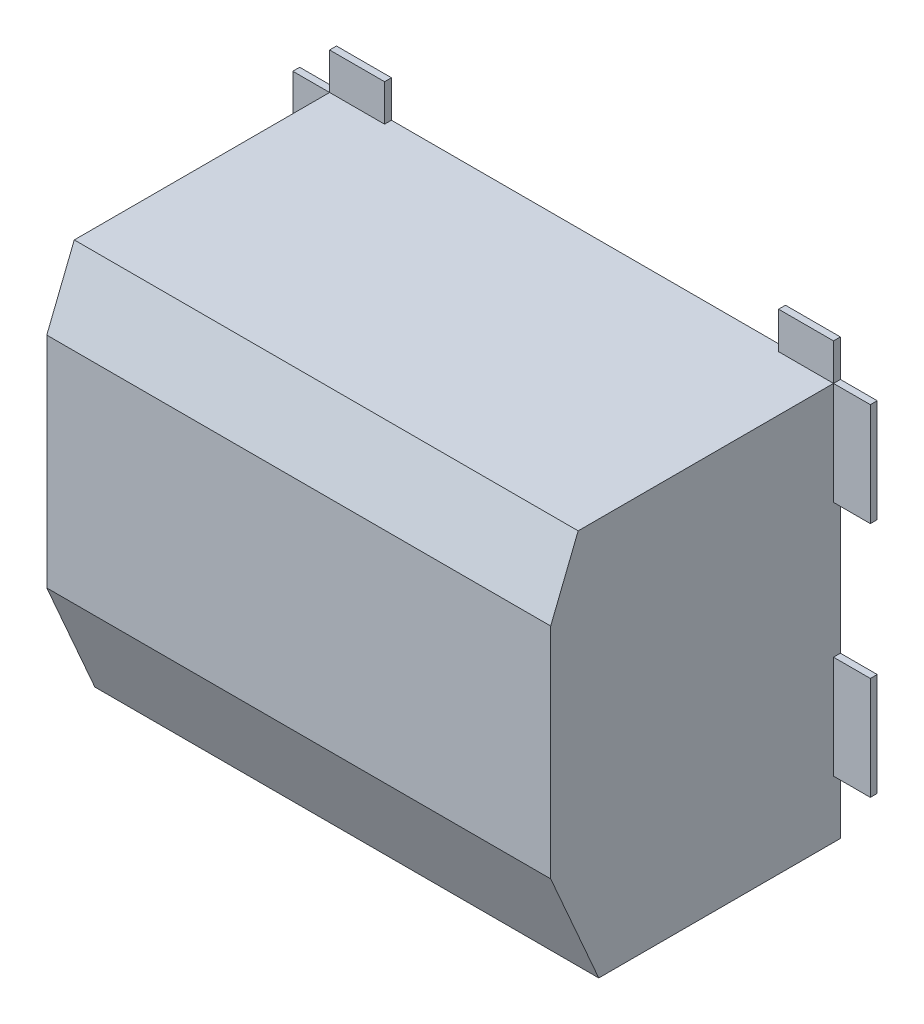
SolidWorks part; units mm, degrees
material "6061-T6 (SS)"
ref_plane "X-Y Datum" through (0, 0, 0) normal (0, 0, 1) x (1, 0, 0)
ref_plane "X-Z Datum" through (0, 0, 0) normal (0, 1, 0) x (1, 0, 0)
ref_plane "Y-Z Datum" through (0, 0, 0) normal (1, 0, 0) x (0, 0, -1)
sketch "Sketch1" plane through (0, 0, 0) normal (0, 0, 1) x (1, 0, 0)
  line L0 (-276.2265, 0) -> (276.2265, 0) construction
  line L1 (-276.2265, 154.041) -> (276.2265, 154.041)
  line L2 (-276.2265, 154.041) -> (-276.2265, -154.041)
  line L3 (-276.2265, -154.041) -> (276.2265, -154.041)
  line L4 (276.2265, 154.041) -> (276.2265, -154.041)
  line L5 (-276.2265, 154.041) -> (276.2265, -154.041) construction
  line L6 (-276.2265, -154.041) -> (276.2265, 154.041) construction
  line L7 (-275.2105, 153.025) -> (-189.6105, 153.025) construction
  line L8 (-275.2105, 153.025) -> (-275.2105, -153.025) construction
  line L9 (-275.2105, -153.025) -> (-189.6105, -153.025) construction
  line L10 (-189.6105, 153.025) -> (-189.6105, -153.025) construction
  line L11 (-275.2105, 153.025) -> (-189.6105, -153.025) construction
  line L12 (-275.2105, -153.025) -> (-189.6105, 153.025) construction
  line L13 (-188.5945, -154.041) -> (-188.5945, 154.041)
  line L14 (-279.4015, 157.216) -> (279.4015, 157.216)
  line L15 (279.4015, 157.216) -> (279.4015, -157.216)
  line L16 (-279.4015, -157.216) -> (279.4015, -157.216)
  line L17 (-279.4015, 157.216) -> (-279.4015, -157.216)
  line L18 (-185.4195, -154.041) -> (-185.4195, 154.041)
  line L19 (-188.5945, 0) -> (-185.4195, 0) construction
  line L20 (-182.2465, 153.025) -> (-182.2465, -153.025) construction
  line L21 (-182.2465, 153.025) -> (-96.6465, 153.025) construction
  line L22 (-96.6465, 153.025) -> (-96.6465, -153.025) construction
  line L23 (-182.2465, -153.025) -> (-96.6465, -153.025) construction
  line L24 (-95.6305, -154.041) -> (-95.6305, 154.041)
  line L25 (-92.4555, -154.041) -> (-92.4555, 154.041)
  line L26 (-89.2825, 153.025) -> (-89.2825, -153.025) construction
  line L27 (-89.2825, 153.025) -> (-3.6825, 153.025) construction
  line L28 (-3.6825, 153.025) -> (-3.6825, -153.025) construction
  line L29 (-89.2825, -153.025) -> (-3.6825, -153.025) construction
  line L30 (-2.6665, -154.041) -> (-2.6665, 154.041)
  line L31 (0.5085, -154.041) -> (0.5085, 154.041)
  line L32 (3.6815, 153.025) -> (3.6815, -153.025) construction
  line L33 (3.6815, 153.025) -> (89.2815, 153.025) construction
  line L34 (89.2815, 153.025) -> (89.2815, -153.025) construction
  line L35 (3.6815, -153.025) -> (89.2815, -153.025) construction
  line L36 (90.2975, -154.041) -> (90.2975, 154.041)
  line L37 (93.4725, -154.041) -> (93.4725, 154.041)
  line L38 (96.6455, 153.025) -> (96.6455, -153.025) construction
  line L39 (96.6455, 153.025) -> (182.2455, 153.025) construction
  line L40 (182.2455, 153.025) -> (182.2455, -153.025) construction
  line L41 (96.6455, -153.025) -> (182.2455, -153.025) construction
  line L42 (183.2615, -154.041) -> (183.2615, 154.041)
  line L43 (186.4365, -154.041) -> (186.4365, 154.041)
  line L44 (-182.2465, -153.025) -> (-96.6465, 153.025) construction
  line L45 (-182.2465, 153.025) -> (-96.6465, -153.025) construction
  line L46 (-89.2825, -153.025) -> (-3.6825, 153.025) construction
  line L47 (-89.2825, 153.025) -> (-3.6825, -153.025) construction
  line L48 (3.6815, -153.025) -> (89.2815, 153.025) construction
  line L49 (3.6815, 153.025) -> (89.2815, -153.025) construction
  line L50 (96.6455, -153.025) -> (182.2455, 153.025) construction
  line L51 (96.6455, 153.025) -> (182.2455, -153.025) construction
  line L52 (-276.2265, -157.216) -> (-276.2265, -208.016)
  line L53 (-279.4015, -157.216) -> (279.4015, -157.216)
  line L54 (-279.4015, -157.216) -> (-279.4015, -210.302)
  line L56 (279.4015, -157.216) -> (279.4015, -397.1906)
  line L58 (276.2265, -157.216) -> (276.2265, -392.7808)
  line L59 (186.4365, -154.041) -> (186.4365, -210.302)
  line L60 (183.2615, -157.216) -> (183.2615, -208.016)
  line L61 (186.4365, 154.041) -> (186.4365, 157.216)
  line L62 (-276.2265, -208.016) -> (276.2265, -392.7808) construction
  line L63 (-276.2265, -208.016) -> (183.2615, -208.016)
  line L64 (-279.4015, -210.302) -> (186.4365, -210.302)
  line L65 (-279.4015, -210.302) -> (279.4015, -397.1906) construction
  point P0 (0, 0)
  point P6 (-232.4105, 0)
  point P23 (-187.007, 0)
  point P24 (-139.4465, 0)
  dimension "D1" = 306.05
  dimension "D2" = 85.6
  dimension "D3" = 1.016
  dimension "D4" = 1.016
  dimension "D5" = 1.016
  dimension "D8" = 45.4035
  dimension "D10" = 89.789
  dimension "D12" = 92.964
  dimension "D13" = 89.79
  dimension "D14" = 50.8
  dimension "D16" = 2.286
  dimension "D6" = 3.175
  dimension "D7" = 3.175
  dimension "D15" = 3.175
  dimension "D9" = 5
  dimension "D11" = 5
extrude "Boss-Extrude1" add sketch "Sketch1" along normal blind 3.175 contours L3 L43 L1 L42 | L54 L64 L59 L53 L60 L63 L52 L16 | L52 L63 L60 L16 | L3 L42 L1 L37 | L3 L36 L1 L31 | L3 L31 L1 L30 | L3 L37 L1 L36 | L3 L30 L1 L25 | L1 L61 L14 L17 L16 L53 L59 L3 L2 | L3 L24 L1 L18 | L3 L13 L1 L2 | L3 L18 L1 L13 | L3 L25 L1 L24
sketch "Sketch2" plane through (0, 0, 3.175) normal (0, 0, 1) x (1, 0, 0)
  line L0 (-188.5945, -154.041) -> (-188.5945, 154.041) construction
  line L1 (-95.6305, -154.041) -> (-95.6305, 154.041) construction
  line L2 (-185.4195, -154.041) -> (-185.4195, 154.041) construction
  line L3 (90.2975, -154.041) -> (90.2975, 154.041) construction
  line L4 (276.2265, 154.041) -> (-276.2265, 154.041)
  line L5 (276.2265, -154.041) -> (276.2265, 154.041)
  line L6 (-276.2265, -154.041) -> (276.2265, -154.041)
  line L7 (-276.2265, 154.041) -> (-276.2265, -154.041)
  line L8 (276.2265, 154.041) -> (-276.2265, 154.041)
  line L9 (276.2265, -154.041) -> (276.2265, 154.041)
  line L10 (-276.2265, -154.041) -> (276.2265, -154.041)
  line L11 (-276.2265, 154.041) -> (-276.2265, -154.041)
  line L12 (-279.4015, -157.216) -> (279.4015, -157.216)
  line L13 (-279.4015, -157.216) -> (279.4015, -157.216) construction
  line L14 (279.4015, 157.216) -> (279.4015, -157.216) construction
  line L15 (-279.4015, 157.216) -> (279.4015, 157.216) construction
  line L16 (-279.4015, -157.216) -> (279.4015, -157.216)
  line L20 (0.5085, -154.041) -> (0.5085, 154.041) construction
  line L21 (-2.6665, -154.041) -> (-2.6665, 154.041) construction
  line L22 (-92.4555, -154.041) -> (-92.4555, 154.041) construction
  line L23 (186.4365, -154.041) -> (186.4365, 154.041) construction
  line L24 (183.2615, -154.041) -> (183.2615, 154.041) construction
  line L25 (93.4725, -154.041) -> (93.4725, 154.041) construction
  line L26 (-188.5945, -154.041) -> (-188.5945, 154.041)
  line L27 (-95.6305, -154.041) -> (-95.6305, 154.041)
  line L28 (-185.4195, -154.041) -> (-185.4195, 154.041)
  line L29 (90.2975, -154.041) -> (90.2975, 154.041)
  line L30 (0.5085, -154.041) -> (0.5085, 154.041)
  line L31 (-2.6665, -154.041) -> (-2.6665, 154.041)
  line L32 (-92.4555, -154.041) -> (-92.4555, 154.041)
  line L33 (186.4365, -154.041) -> (186.4365, 154.041)
  line L34 (183.2615, -154.041) -> (183.2615, 154.041)
  line L35 (93.4725, -154.041) -> (93.4725, 154.041)
  line L36 (-279.4015, 157.216) -> (-279.4015, -157.216) construction
  line L37 (-279.4015, -157.216) -> (279.4015, -157.216) construction
  line L38 (-279.4015, -157.216) -> (-279.4015, -210.302) construction
  line L41 (-276.2265, -157.216) -> (-276.2265, -208.016) construction
  line L44 (-276.2265, 154.041) -> (276.2265, 154.041) construction
  line L45 (276.2265, 154.041) -> (276.2265, -154.041) construction
  line L46 (-276.2265, -154.041) -> (276.2265, -154.041) construction
  line L47 (-276.2265, 154.041) -> (-276.2265, -154.041) construction
  line L48 (-188.5945, -154.041) -> (-188.5945, 154.041)
  line L49 (-95.6305, -154.041) -> (-95.6305, 154.041)
  line L50 (-185.4195, -154.041) -> (-185.4195, 154.041)
  line L51 (-279.4015, -157.216) -> (279.4015, -157.216)
  line L52 (279.4015, 157.216) -> (279.4015, -157.216)
  line L53 (-279.4015, 157.216) -> (279.4015, 157.216)
  line L54 (-279.4015, 157.216) -> (-279.4015, -157.216)
  line L55 (-279.4015, -157.216) -> (279.4015, -157.216)
  line L56 (-279.4015, -157.216) -> (-279.4015, -210.302)
  line L59 (90.2975, -154.041) -> (90.2975, 154.041)
  line L60 (0.5085, -154.041) -> (0.5085, 154.041)
  line L61 (-2.6665, -154.041) -> (-2.6665, 154.041)
  line L62 (-92.4555, -154.041) -> (-92.4555, 154.041)
  line L63 (186.4365, -154.041) -> (186.4365, 154.041)
  line L64 (183.2615, -154.041) -> (183.2615, 154.041)
  line L65 (93.4725, -154.041) -> (93.4725, 154.041)
  line L66 (-276.2265, -157.216) -> (-276.2265, -208.016)
  line L67 (-279.4015, -210.302) -> (186.4365, -210.302) construction
  line L69 (-276.2265, 154.041) -> (276.2265, 154.041)
  line L70 (276.2265, 154.041) -> (276.2265, -154.041)
  line L71 (-276.2265, -154.041) -> (276.2265, -154.041)
  line L72 (-276.2265, 154.041) -> (-276.2265, -154.041)
  line L73 (183.2615, -157.216) -> (183.2615, -208.016) construction
  line L74 (186.4365, 154.041) -> (186.4365, 157.216) construction
  line L75 (186.4365, -154.041) -> (186.4365, -210.302) construction
  line L76 (-188.5945, -154.041) -> (-188.5945, 154.041)
  line L77 (-95.6305, -154.041) -> (-95.6305, 154.041)
  line L78 (-185.4195, -154.041) -> (-185.4195, 154.041)
  line L79 (-279.4015, -157.216) -> (279.4015, -157.216)
  line L80 (279.4015, 157.216) -> (279.4015, -157.216)
  line L81 (-279.4015, 157.216) -> (279.4015, 157.216)
  line L82 (-279.4015, 157.216) -> (-279.4015, -157.216)
  line L83 (-279.4015, -157.216) -> (279.4015, -157.216)
  line L84 (-279.4015, -157.216) -> (-279.4015, -210.302)
  line L85 (-276.2265, -208.016) -> (183.2615, -208.016) construction
  line L87 (90.2975, -154.041) -> (90.2975, 154.041)
  line L88 (0.5085, -154.041) -> (0.5085, 154.041)
  line L89 (-2.6665, -154.041) -> (-2.6665, 154.041)
  line L90 (-92.4555, -154.041) -> (-92.4555, 154.041)
  line L91 (183.2615, -154.041) -> (183.2615, 154.041)
  line L92 (93.4725, -154.041) -> (93.4725, 154.041)
  line L93 (183.2615, -157.216) -> (183.2615, -208.016)
  line L94 (-276.2265, -157.216) -> (-276.2265, -208.016)
  line L97 (186.4365, 154.041) -> (186.4365, 157.216)
  line L98 (186.4365, -154.041) -> (186.4365, 154.041)
  line L99 (186.4365, -154.041) -> (186.4365, -210.302)
  line L100 (-276.2265, 154.041) -> (276.2265, 154.041)
  line L101 (276.2265, 154.041) -> (276.2265, -154.041)
  line L102 (-276.2265, -154.041) -> (276.2265, -154.041)
  line L103 (-276.2265, 154.041) -> (-276.2265, -154.041)
  line L104 (-188.5945, -154.041) -> (-188.5945, 154.041)
  line L106 (-95.6305, -154.041) -> (-95.6305, 154.041)
  line L107 (-185.4195, -154.041) -> (-185.4195, 154.041)
  line L108 (-279.4015, -157.216) -> (279.4015, -157.216)
  line L109 (279.4015, 157.216) -> (279.4015, -157.216)
  line L110 (-279.4015, 157.216) -> (279.4015, 157.216)
  line L111 (-279.4015, 157.216) -> (-279.4015, -157.216)
  line L112 (-279.4015, -157.216) -> (279.4015, -157.216)
  line L113 (186.4365, 154.041) -> (186.4365, 157.216)
  line L114 (186.4365, -154.041) -> (186.4365, 154.041)
  line L115 (186.4365, -154.041) -> (186.4365, -210.302)
  line L116 (-279.4015, -210.302) -> (186.4365, -210.302)
  line L117 (-279.4015, -157.216) -> (-279.4015, -210.302)
  line L118 (90.2975, -154.041) -> (90.2975, 154.041)
  line L119 (0.5085, -154.041) -> (0.5085, 154.041)
  line L120 (-2.6665, -154.041) -> (-2.6665, 154.041)
  line L121 (-92.4555, -154.041) -> (-92.4555, 154.041)
  line L122 (183.2615, -154.041) -> (183.2615, 154.041)
  line L123 (93.4725, -154.041) -> (93.4725, 154.041)
  line L124 (183.2615, -157.216) -> (183.2615, -208.016)
  line L125 (-276.2265, -208.016) -> (183.2615, -208.016)
  line L126 (-276.2265, -157.216) -> (-276.2265, -208.016)
  line L128 (-276.2265, 154.041) -> (276.2265, 154.041)
  line L129 (276.2265, 154.041) -> (276.2265, -154.041)
  line L130 (-276.2265, -154.041) -> (276.2265, -154.041)
  line L131 (-276.2265, 154.041) -> (-276.2265, -154.041)
  line M9 (186.4365, 157.216) -> (-279.4015, 157.216)
  line M10 (-279.4015, 157.216) -> (-279.4015, -210.302)
  line M86 (186.4365, -210.302) -> (186.4365, 157.216)
  line M120 (-279.4015, -210.302) -> (186.4365, -210.302)
  dimension "D1" = 0
  dimension "D2" = 0
extrude "Boss-Extrude2" add sketch "Sketch2" along normal blind 200.6 contours L125 L66 L16 L83 L93 M10 M120 M86 | L16 L55 L83 L10 L11 L8 M10 M86 M9 | L34 L10 L8 M86 | L10 L35 L8 L29 | L10 L28 L8 L26 | L10 L32 L8 L27 | L31 L10 L30 L8 | L10 L26 L8 L11 | L28 L10 L27 L8 | L32 L10 L31 L8 | L30 L10 L29 L8 | L35 L10 L34 L8 | L66 L125 L93 L55
sketch "Sketch11" plane through (0, 0, 203.775) normal (0, 0, 1) x (1, 0, 0)
  line L0 (-188.5945, -154.041) -> (-188.5945, 154.041) construction
  line L2 (-95.6305, -154.041) -> (-95.6305, 154.041) construction
  line L3 (-185.4195, -154.041) -> (-185.4195, 154.041) construction
  line L4 (186.4365, -210.302) -> (186.4365, 157.216)
  line L5 (186.4365, 157.216) -> (-279.4015, 157.216)
  line L6 (-279.4015, 157.216) -> (-279.4015, -210.302)
  line L7 (-279.4015, -210.302) -> (186.4365, -210.302)
  line L8 (186.4365, -210.302) -> (186.4365, 157.216)
  line L9 (186.4365, 157.216) -> (-279.4015, 157.216)
  line L10 (-279.4015, 157.216) -> (-279.4015, -210.302)
  line L11 (-279.4015, -210.302) -> (186.4365, -210.302)
  line L12 (-279.4015, -157.216) -> (279.4015, -157.216) construction
  line L14 (-279.4015, 157.216) -> (279.4015, 157.216) construction
  line L15 (-279.4015, 157.216) -> (-279.4015, -157.216) construction
  line L16 (-279.4015, -157.216) -> (279.4015, -157.216) construction
  line L17 (186.4365, 154.041) -> (186.4365, 157.216) construction
  line L18 (186.4365, -154.041) -> (186.4365, 154.041) construction
  line L19 (186.4365, -154.041) -> (186.4365, -210.302) construction
  line L20 (-279.4015, -210.302) -> (186.4365, -210.302) construction
  line L21 (-279.4015, -157.216) -> (-279.4015, -210.302) construction
  line L22 (90.2975, -154.041) -> (90.2975, 154.041) construction
  line L23 (0.5085, -154.041) -> (0.5085, 154.041) construction
  line L24 (-2.6665, -154.041) -> (-2.6665, 154.041) construction
  line L25 (-92.4555, -154.041) -> (-92.4555, 154.041) construction
  line L26 (183.2615, -154.041) -> (183.2615, 154.041) construction
  line L27 (93.4725, -154.041) -> (93.4725, 154.041) construction
  line L28 (183.2615, -157.216) -> (183.2615, -208.016) construction
  line L29 (-276.2265, -208.016) -> (183.2615, -208.016) construction
  line L30 (-276.2265, -157.216) -> (-276.2265, -208.016) construction
  line L32 (-276.2265, 154.041) -> (276.2265, 154.041) construction
  line L34 (-276.2265, -154.041) -> (276.2265, -154.041) construction
  line L35 (-276.2265, 154.041) -> (-276.2265, -154.041) construction
  line L36 (-188.5945, -154.041) -> (-188.5945, 154.041)
  line L37 (183.2615, -157.216) -> (183.2615, -154.041)
  line L38 (-95.6305, -154.041) -> (-95.6305, 154.041)
  line L39 (-185.4195, -154.041) -> (-185.4195, 154.041)
  line L40 (-279.4015, -157.216) -> (186.4365, -157.216)
  line L42 (-279.4015, 157.216) -> (186.4365, 157.216)
  line L43 (-279.4015, 157.216) -> (-279.4015, -157.216)
  line L44 (-279.4015, -157.216) -> (186.4365, -157.216)
  line L45 (186.4365, 154.041) -> (186.4365, 157.216)
  line L46 (186.4365, -154.041) -> (186.4365, 154.041)
  line L47 (186.4365, -154.041) -> (186.4365, -210.302)
  line L48 (-279.4015, -210.302) -> (186.4365, -210.302)
  line L49 (-279.4015, -157.216) -> (-279.4015, -210.302)
  line L50 (90.2975, -154.041) -> (90.2975, 154.041)
  line L51 (0.5085, -154.041) -> (0.5085, 154.041)
  line L52 (-2.6665, -154.041) -> (-2.6665, 154.041)
  line L53 (-92.4555, -154.041) -> (-92.4555, 154.041)
  line L54 (183.2615, -154.041) -> (183.2615, 154.041)
  line L55 (93.4725, -154.041) -> (93.4725, 154.041)
  line L56 (183.2615, -157.216) -> (183.2615, -208.016)
  line L57 (-276.2265, -208.016) -> (183.2615, -208.016)
  line L58 (-276.2265, -157.216) -> (-276.2265, -208.016)
  line L59 (-276.2265, -157.216) -> (-276.2265, -154.041)
  line L60 (-276.2265, 154.041) -> (186.4365, 154.041)
  line L62 (-276.2265, -154.041) -> (186.4365, -154.041)
  line L63 (-276.2265, 154.041) -> (-276.2265, -154.041)
  line M21 (186.4365, -210.302) -> (186.4365, 157.216)
  line M22 (186.4365, 157.216) -> (-279.4015, 157.216)
  line M23 (-279.4015, 157.216) -> (-279.4015, -210.302)
  line M24 (-279.4015, -210.302) -> (186.4365, -210.302)
  dimension "D1" = 0
extrude "Boss-Extrude8" add sketch "Sketch11" along normal blind 64.05 contours L60 L63 L62 L36 | L39 L62 L38 L60 | L36 L62 L39 L60 | L62 L59 L44 L37 | L44 L58 L57 L56 | L53 L62 L52 L60 | L38 L62 L53 L60 | L51 L62 L50 L60 | L52 L62 L51 L60 | L55 L62 L54 L60 | L50 L62 L55 L60 | L54 L62 L60 M21 | L62 L37 L40 L8 | L58 L40 L10 L56 L57 M24 M21 | L63 L60 L40 L59 M21 M22 M23
sketch "Sketch10" plane through (0, 0, 0) normal (0, 0, 1) x (1, 0, 0)
  line L1 (186.4365, 157.216) -> (220.4725, 157.216)
  line L2 (186.4365, 157.216) -> (186.4365, 61.966)
  line L3 (186.4365, 61.966) -> (220.4725, 61.966)
  line L4 (186.4365, -210.302) -> (186.4365, 157.216)
  line L5 (-279.4015, -210.302) -> (186.4365, -210.302)
  line L6 (-279.4015, 157.216) -> (-279.4015, -210.302)
  line L7 (186.4365, 157.216) -> (-279.4015, 157.216)
  line L8 (186.4365, -210.302) -> (186.4365, 157.216)
  line L10 (-279.4015, 157.216) -> (-279.4015, -210.302)
  line L11 (186.4365, 157.216) -> (-279.4015, 157.216)
  line L12 (220.4725, 157.216) -> (220.4725, 61.966)
  line L14 (-276.2265, -157.216) -> (183.2615, -157.216)
  line L15 (186.4365, -157.216) -> (220.4725, -157.216)
  line L16 (186.4365, -157.216) -> (186.4365, -61.966)
  line L17 (186.4365, -61.966) -> (220.4725, -61.966)
  line L18 (220.4725, -157.216) -> (220.4725, -61.966)
  line L19 (186.4365, 157.216) -> (135.6365, 157.216)
  line L20 (186.4365, 157.216) -> (186.4365, 191.252)
  line L21 (186.4365, 191.252) -> (135.6365, 191.252)
  line L22 (135.6365, 157.216) -> (135.6365, 191.252)
  line L26 (-279.4015, -210.302) -> (186.4365, -210.302)
  dimension "D2" = 34.036
  dimension "D3" = 95.25
  dimension "D4" = 50.8
  dimension "D1" = 0
extrude "Boss-Extrude7" add sketch "Sketch10" along normal blind 6.35 contours L12 L1 L2 L3 | L15 L18 L17 L8 | L22 L11 L20 L21
ref_plane "Plane1" through (-46.4825, 0, 0) normal (-1, 0, 0) x (0, 0, 1)
mirror "Mirror1" about plane through (-46.4825, 0, 0) normal (-1, 0, 0) of "Boss-Extrude7"
sketch "Sketch12" plane through (186.4365, 0, 0) normal (1, 0, 0) x (0, 0, -1)
  line L0 (-223.375, -210.302) -> (-267.825, -108.702)
  line L1 (-267.825, 93.716) -> (-242.425, 157.216)
  line L10 (0, -210.302) -> (0, -157.216)
  line L11 (0, -157.216) -> (-6.35, -157.216)
  line L12 (-6.35, -157.216) -> (-6.35, -61.966)
  line L13 (-6.35, -61.966) -> (0, -61.966)
  line L14 (0, -61.966) -> (0, 61.966)
  line L15 (0, 61.966) -> (-6.35, 61.966)
  line L16 (-6.35, 61.966) -> (-6.35, 157.216)
  line L17 (-6.35, 157.216) -> (-267.825, 157.216)
  line L18 (-267.825, 157.216) -> (-267.825, -210.302)
  line L19 (-267.825, -210.302) -> (0, -210.302)
  line L20 (0, -210.302) -> (0, -157.216)
  line L21 (0, -157.216) -> (-6.35, -157.216)
  line L22 (-6.35, -157.216) -> (-6.35, -61.966)
  line L23 (-6.35, -61.966) -> (0, -61.966)
  line L24 (0, -61.966) -> (0, 61.966)
  line L25 (0, 61.966) -> (-6.35, 61.966)
  line L26 (-6.35, 61.966) -> (-6.35, 157.216)
  line L27 (-6.35, 157.216) -> (-267.825, 157.216)
  line L28 (-267.825, 157.216) -> (-267.825, -210.302)
  line L29 (-267.825, -210.302) -> (0, -210.302)
  line M18 (-6.35, 157.216) -> (-267.825, 157.216)
  line M19 (-267.825, 157.216) -> (-267.825, -210.302)
  line M20 (-267.825, -210.302) -> (0, -210.302)
  dimension "D2" = 44.45
  dimension "D3" = 101.6
  dimension "D4" = 25.4
  dimension "D5" = 63.5
  dimension "D1" = 0
extrude "Cut-Extrude1" cut sketch "Sketch12" against normal through all contours L0 M20 M19 | L1 M19 M18
sketch "Sketch13" plane through (0, 157.216, 0) normal (0, 1, 0) x (1, 0, 0)
  circle A0 centre (-238.9105, -118.4317) radius 5 construction
  circle A1 centre (-238.9105, -129.4317) radius 5 construction
  circle A2 centre (-238.9105, -140.4317) radius 5 construction
  circle A3 centre (-227.4105, -140.4317) radius 5 construction
  circle A4 centre (-227.4105, -129.4317) radius 5 construction
  circle A5 centre (-227.4105, -118.4317) radius 5 construction
  circle A6 centre (-215.9105, -118.4317) radius 5 construction
  circle A7 centre (-215.9105, -129.4317) radius 5 construction
  circle A8 centre (-215.9105, -140.4317) radius 5 construction
  circle A9 centre (-238.9105, -118.4317) radius 5
  circle A10 centre (-238.9105, -129.4317) radius 5
  circle A11 centre (-238.9105, -140.4317) radius 5
  circle A12 centre (-227.4105, -140.4317) radius 5
  circle A13 centre (-227.4105, -129.4317) radius 5
  circle A14 centre (-227.4105, -118.4317) radius 5
  circle A15 centre (-215.9105, -118.4317) radius 5
  circle A16 centre (-215.9105, -129.4317) radius 5
  circle A17 centre (-215.9105, -140.4317) radius 5
  circle A18 centre (-215.9105, -53.2317) radius 5 construction
  circle A19 centre (-215.9105, -53.2317) radius 5
  circle A20 centre (-215.9105, -75.2317) radius 5 construction
  circle A21 centre (-227.4105, -75.2317) radius 5 construction
  circle A22 centre (-238.9105, -75.2317) radius 5 construction
  circle A23 centre (-238.9105, -64.2317) radius 5 construction
  circle A24 centre (-227.4105, -64.2317) radius 5 construction
  circle A25 centre (-215.9105, -64.2317) radius 5 construction
  circle A26 centre (-227.4105, -53.2317) radius 5 construction
  circle A27 centre (-238.9105, -53.2317) radius 5 construction
  circle A28 centre (-215.9105, -75.2317) radius 5
  circle A29 centre (-227.4105, -75.2317) radius 5
  circle A30 centre (-238.9105, -75.2317) radius 5
  circle A31 centre (-238.9105, -64.2317) radius 5
  circle A32 centre (-227.4105, -64.2317) radius 5
  circle A33 centre (-215.9105, -64.2317) radius 5
  circle A34 centre (-215.9105, -53.2317) radius 5
  circle A35 centre (-227.4105, -53.2317) radius 5
  circle A36 centre (-238.9105, -53.2317) radius 5
  circle A37 centre (-145.525, -140.4317) radius 5 construction
  circle A38 centre (-145.525, -129.4317) radius 5 construction
  circle A39 centre (-145.525, -118.4317) radius 5 construction
  circle A40 centre (-157.025, -118.4317) radius 5 construction
  circle A41 centre (-157.025, -129.4317) radius 5 construction
  circle A42 centre (-157.025, -140.4317) radius 5 construction
  circle A43 centre (-145.525, -140.4317) radius 5
  circle A44 centre (-145.525, -129.4317) radius 5
  circle A45 centre (-145.525, -118.4317) radius 5
  circle A46 centre (-157.025, -118.4317) radius 5
  circle A47 centre (-157.025, -129.4317) radius 5
  circle A48 centre (-157.025, -140.4317) radius 5
  circle A49 centre (-134.025, -118.4317) radius 5 construction
  circle A50 centre (-134.025, -140.4317) radius 5 construction
  circle A51 centre (-134.025, -129.4317) radius 5 construction
  circle A52 centre (-134.025, -118.4317) radius 5
  circle A53 centre (-134.025, -140.4317) radius 5
  circle A54 centre (-134.025, -129.4317) radius 5
  circle A55 centre (-157.025, -75.2317) radius 5 construction
  circle A56 centre (-145.525, -75.2317) radius 5 construction
  circle A57 centre (-134.025, -75.2317) radius 5 construction
  circle A58 centre (-157.025, -75.2317) radius 5
  circle A59 centre (-145.525, -75.2317) radius 5
  circle A60 centre (-134.025, -75.2317) radius 5
  circle A61 centre (-134.025, -53.2317) radius 5 construction
  circle A62 centre (-145.525, -53.2317) radius 5 construction
  circle A63 centre (-157.025, -53.2317) radius 5 construction
  circle A64 centre (-157.025, -64.2317) radius 5 construction
  circle A65 centre (-134.025, -64.2317) radius 5 construction
  circle A66 centre (-145.525, -64.2317) radius 5 construction
  circle A67 centre (-134.025, -53.2317) radius 5
  circle A68 centre (-145.525, -53.2317) radius 5
  circle A69 centre (-157.025, -53.2317) radius 5
  circle A70 centre (-157.025, -64.2317) radius 5
  circle A71 centre (-134.025, -64.2317) radius 5
  circle A72 centre (-145.525, -64.2317) radius 5
extrude "Cut-Extrude2" [suppressed] cut sketch "Sketch13" against normal up to surface (3.175 mm away) contours A35 | A36 | A31 | A32 | A33 | A30 | A29 | A28 | A10 | A13 | A11 | A12 | A17 | A16 | A15 | A19 | A9 | A14
pattern_linear "LPattern1" [suppressed] count 3 spacing 185.92
sketch "Sketch14" plane through (0, 157.216, 0) normal (0, 1, 0) x (1, 0, 0)
  circle A1 centre (-215.9105, -53.2317) radius 5
  circle A2 centre (-215.9105, -53.2317) radius 5
  circle A3 centre (-215.9105, -140.4317) radius 5
  circle A4 centre (-215.9105, -140.4317) radius 5
  circle A5 centre (-215.9105, -129.4317) radius 5
  circle A6 centre (-215.9105, -129.4317) radius 5
  circle A7 centre (-215.9105, -118.4317) radius 5
  circle A8 centre (-215.9105, -118.4317) radius 5
  circle A9 centre (-227.4105, -118.4317) radius 5
  circle A10 centre (-227.4105, -118.4317) radius 5
  circle A11 centre (-227.4105, -129.4317) radius 5
  circle A12 centre (-227.4105, -129.4317) radius 5
  circle A13 centre (-227.4105, -140.4317) radius 5
  circle A14 centre (-227.4105, -140.4317) radius 5
  circle A15 centre (-238.9105, -140.4317) radius 5
  circle A16 centre (-238.9105, -140.4317) radius 5
  circle A17 centre (-238.9105, -129.4317) radius 5
  circle A18 centre (-238.9105, -129.4317) radius 5
  circle A19 centre (-238.9105, -118.4317) radius 5
  circle A20 centre (-238.9105, -118.4317) radius 5
  circle A21 centre (-227.4105, -75.2317) radius 5
  circle A22 centre (-227.4105, -75.2317) radius 5
  circle A23 centre (-215.9105, -75.2317) radius 5
  circle A24 centre (-215.9105, -75.2317) radius 5
  circle A25 centre (-238.9105, -53.2317) radius 5
  circle A26 centre (-238.9105, -53.2317) radius 5
  circle A27 centre (-227.4105, -53.2317) radius 5
  circle A28 centre (-227.4105, -53.2317) radius 5
  circle A29 centre (-215.9105, -53.2317) radius 5
  circle A30 centre (-215.9105, -53.2317) radius 5
  circle A31 centre (-215.9105, -64.2317) radius 5
  circle A32 centre (-215.9105, -64.2317) radius 5
  circle A33 centre (-227.4105, -64.2317) radius 5
  circle A34 centre (-227.4105, -64.2317) radius 5
  circle A35 centre (-238.9105, -64.2317) radius 5
  circle A36 centre (-238.9105, -64.2317) radius 5
  circle A37 centre (-238.9105, -75.2317) radius 5
  circle A38 centre (-238.9105, -75.2317) radius 5
  circle A39 centre (-134.025, -118.4317) radius 5
  circle A40 centre (-134.025, -118.4317) radius 5
  circle A41 centre (-157.025, -140.4317) radius 5
  circle A42 centre (-157.025, -140.4317) radius 5
  circle A43 centre (-157.025, -129.4317) radius 5
  circle A44 centre (-157.025, -129.4317) radius 5
  circle A45 centre (-157.025, -118.4317) radius 5
  circle A46 centre (-157.025, -118.4317) radius 5
  circle A47 centre (-145.525, -118.4317) radius 5
  circle A48 centre (-145.525, -118.4317) radius 5
  circle A49 centre (-145.525, -129.4317) radius 5
  circle A50 centre (-145.525, -129.4317) radius 5
  circle A51 centre (-145.525, -140.4317) radius 5
  circle A52 centre (-145.525, -140.4317) radius 5
  circle A53 centre (-134.025, -75.2317) radius 5
  circle A54 centre (-134.025, -75.2317) radius 5
  circle A55 centre (-145.525, -75.2317) radius 5
  circle A56 centre (-145.525, -75.2317) radius 5
  circle A57 centre (-157.025, -75.2317) radius 5
  circle A58 centre (-157.025, -75.2317) radius 5
  circle A59 centre (-134.025, -129.4317) radius 5
  circle A60 centre (-134.025, -129.4317) radius 5
  circle A61 centre (-134.025, -140.4317) radius 5
  circle A62 centre (-134.025, -140.4317) radius 5
  circle A63 centre (-145.525, -64.2317) radius 5
  circle A64 centre (-145.525, -64.2317) radius 5
  circle A65 centre (-134.025, -64.2317) radius 5
  circle A66 centre (-134.025, -64.2317) radius 5
  circle A67 centre (-157.025, -64.2317) radius 5
  circle A68 centre (-157.025, -64.2317) radius 5
  circle A69 centre (-157.025, -53.2317) radius 5
  circle A70 centre (-157.025, -53.2317) radius 5
  circle A71 centre (-145.525, -53.2317) radius 5
  circle A72 centre (-145.525, -53.2317) radius 5
  circle A73 centre (-134.025, -53.2317) radius 5
  circle A74 centre (-134.025, -53.2317) radius 5
  dimension "D1" = 0
  dimension "D2" = 0
  dimension "D3" = 0
  dimension "D4" = 0
  dimension "D5" = 0
  dimension "D6" = 0
  dimension "D7" = 0
  dimension "D8" = 0
  dimension "D9" = 0
  dimension "D10" = 0
  dimension "D11" = 0
  dimension "D12" = 0
  dimension "D13" = 0
  dimension "D14" = 0
  dimension "D15" = 0
  dimension "D16" = 0
  dimension "D17" = 0
  dimension "D18" = 0
  dimension "D19" = 0
  dimension "D20" = 0
  dimension "D21" = 0
  dimension "D22" = 0
  dimension "D23" = 0
  dimension "D24" = 0
  dimension "D25" = 0
  dimension "D26" = 0
  dimension "D27" = 0
  dimension "D28" = 0
  dimension "D29" = 0
  dimension "D30" = 0
  dimension "D31" = 0
  dimension "D32" = 0
  dimension "D33" = 0
  dimension "D34" = 0
  dimension "D35" = 0
  dimension "D36" = 0
  dimension "D37" = 0
extrude "Cut-Extrude3" [suppressed] cut sketch "Sketch14" against normal up to surface (3.175 mm away) contours A42 | A52 | A62 | A60 | A50 | A44 | A46 | A48 | A40 | A56 | A54 | A66 | A64 | A68 | A70 | A72 | A74 | A58
pattern_linear "LPattern2" [suppressed] count 2 spacing 185.92
sketch "Sketch16" plane through (0, -157.216, 0) normal (0, -1, 0) x (1, 0, 0)
  circle A0 centre (-215.9105, 140.4317) radius 5 construction
  circle A1 centre (-227.4105, 140.4317) radius 5 construction
  circle A2 centre (-238.9105, 140.4317) radius 5 construction
  circle A3 centre (-215.9105, 129.4317) radius 5 construction
  circle A4 centre (-238.9105, 129.4317) radius 5 construction
  circle A5 centre (-227.4105, 129.4317) radius 5 construction
  circle A6 centre (-215.9105, 118.4317) radius 5 construction
  circle A7 centre (-227.4105, 118.4317) radius 5 construction
  circle A8 centre (-238.9105, 118.4317) radius 5 construction
  circle A9 centre (-215.9105, 107.4317) radius 5 construction
  circle A10 centre (-227.4105, 107.4317) radius 5 construction
  circle A11 centre (-238.9105, 107.4317) radius 5 construction
  circle A12 centre (-215.9105, 96.4317) radius 5 construction
  circle A13 centre (-227.4105, 96.4317) radius 5 construction
  circle A14 centre (-238.9105, 96.4317) radius 5 construction
  circle A15 centre (-215.9105, 85.4317) radius 5 construction
  circle A16 centre (-227.4105, 74.4317) radius 5 construction
  circle A17 centre (-227.4105, 85.4317) radius 5 construction
  circle A18 centre (-238.9105, 85.4317) radius 5 construction
  circle A19 centre (-238.9105, 74.4317) radius 5 construction
  circle A20 centre (-227.4105, 63.4317) radius 5 construction
  circle A21 centre (-238.9105, 63.4317) radius 5 construction
  circle A22 centre (-238.9105, 52.4317) radius 5 construction
  circle A23 centre (-238.9105, 41.4317) radius 5 construction
  circle A24 centre (-238.9105, 30.4317) radius 5 construction
  circle A25 centre (-227.4105, 30.4317) radius 5 construction
  circle A26 centre (-215.9105, 30.4317) radius 5 construction
  circle A27 centre (-215.9105, 41.4317) radius 5 construction
  circle A28 centre (-227.4105, 41.4317) radius 5 construction
  circle A29 centre (-227.4105, 52.4317) radius 5 construction
  circle A30 centre (-215.9105, 52.4317) radius 5 construction
  circle A31 centre (-215.9105, 74.4317) radius 5 construction
  circle A32 centre (-215.9105, 63.4317) radius 5 construction
  circle A33 centre (-215.9105, 140.4317) radius 5
  circle A34 centre (-227.4105, 140.4317) radius 5
  circle A35 centre (-238.9105, 140.4317) radius 5
  circle A36 centre (-215.9105, 129.4317) radius 5
  circle A37 centre (-238.9105, 129.4317) radius 5
  circle A38 centre (-227.4105, 129.4317) radius 5
  circle A39 centre (-215.9105, 118.4317) radius 5
  circle A40 centre (-227.4105, 118.4317) radius 5
  circle A41 centre (-238.9105, 118.4317) radius 5
  circle A42 centre (-215.9105, 107.4317) radius 5
  circle A43 centre (-227.4105, 107.4317) radius 5
  circle A44 centre (-238.9105, 107.4317) radius 5
  circle A45 centre (-215.9105, 96.4317) radius 5
  circle A46 centre (-227.4105, 96.4317) radius 5
  circle A47 centre (-238.9105, 96.4317) radius 5
  circle A48 centre (-215.9105, 85.4317) radius 5
  circle A49 centre (-227.4105, 74.4317) radius 5
  circle A50 centre (-227.4105, 85.4317) radius 5
  circle A51 centre (-238.9105, 85.4317) radius 5
  circle A52 centre (-238.9105, 74.4317) radius 5
  circle A53 centre (-227.4105, 63.4317) radius 5
  circle A54 centre (-238.9105, 63.4317) radius 5
  circle A55 centre (-238.9105, 52.4317) radius 5
  circle A56 centre (-238.9105, 41.4317) radius 5
  circle A57 centre (-238.9105, 30.4317) radius 5
  circle A58 centre (-227.4105, 30.4317) radius 5
  circle A59 centre (-215.9105, 30.4317) radius 5
  circle A60 centre (-215.9105, 41.4317) radius 5
  circle A61 centre (-227.4105, 41.4317) radius 5
  circle A62 centre (-227.4105, 52.4317) radius 5
  circle A63 centre (-215.9105, 52.4317) radius 5
  circle A64 centre (-215.9105, 74.4317) radius 5
  circle A65 centre (-215.9105, 63.4317) radius 5
  circle A66 centre (-134.025, 140.4317) radius 5 construction
  circle A67 centre (-145.525, 140.4317) radius 5 construction
  circle A68 centre (-157.025, 140.4317) radius 5 construction
  circle A69 centre (-134.025, 129.4317) radius 5 construction
  circle A70 centre (-145.525, 129.4317) radius 5 construction
  circle A71 centre (-157.025, 129.4317) radius 5 construction
  circle A72 centre (-134.025, 118.4317) radius 5 construction
  circle A73 centre (-145.525, 118.4317) radius 5 construction
  circle A74 centre (-157.025, 118.4317) radius 5 construction
  circle A75 centre (-134.025, 107.4317) radius 5 construction
  circle A76 centre (-145.525, 107.4317) radius 5 construction
  circle A77 centre (-157.025, 107.4317) radius 5 construction
  circle A78 centre (-134.025, 96.4317) radius 5 construction
  circle A79 centre (-145.525, 96.4317) radius 5 construction
  circle A80 centre (-157.025, 96.4317) radius 5 construction
  circle A81 centre (-134.025, 85.4317) radius 5 construction
  circle A82 centre (-145.525, 85.4317) radius 5 construction
  circle A83 centre (-157.025, 85.4317) radius 5 construction
  circle A84 centre (-134.025, 74.4317) radius 5 construction
  circle A85 centre (-145.525, 74.4317) radius 5 construction
  circle A86 centre (-157.025, 74.4317) radius 5 construction
  circle A87 centre (-134.025, 63.4317) radius 5 construction
  circle A88 centre (-145.525, 63.4317) radius 5 construction
  circle A89 centre (-157.025, 63.4317) radius 5 construction
  circle A90 centre (-134.025, 52.4317) radius 5 construction
  circle A91 centre (-145.525, 52.4317) radius 5 construction
  circle A92 centre (-157.025, 52.4317) radius 5 construction
  circle A93 centre (-134.025, 41.4317) radius 5 construction
  circle A94 centre (-145.525, 41.4317) radius 5 construction
  circle A95 centre (-157.025, 41.4317) radius 5 construction
  circle A96 centre (-134.025, 30.4317) radius 5 construction
  circle A97 centre (-145.525, 30.4317) radius 5 construction
  circle A98 centre (-157.025, 30.4317) radius 5 construction
  circle A99 centre (-134.025, 140.4317) radius 5
  circle A100 centre (-145.525, 140.4317) radius 5
  circle A101 centre (-157.025, 140.4317) radius 5
  circle A102 centre (-134.025, 129.4317) radius 5
  circle A103 centre (-145.525, 129.4317) radius 5
  circle A104 centre (-157.025, 129.4317) radius 5
  circle A105 centre (-134.025, 118.4317) radius 5
  circle A106 centre (-145.525, 118.4317) radius 5
  circle A107 centre (-157.025, 118.4317) radius 5
  circle A108 centre (-134.025, 107.4317) radius 5
  circle A109 centre (-145.525, 107.4317) radius 5
  circle A110 centre (-157.025, 107.4317) radius 5
  circle A111 centre (-134.025, 96.4317) radius 5
  circle A112 centre (-145.525, 96.4317) radius 5
  circle A113 centre (-157.025, 96.4317) radius 5
  circle A114 centre (-134.025, 85.4317) radius 5
  circle A115 centre (-145.525, 85.4317) radius 5
  circle A116 centre (-157.025, 85.4317) radius 5
  circle A117 centre (-134.025, 74.4317) radius 5
  circle A118 centre (-145.525, 74.4317) radius 5
  circle A119 centre (-157.025, 74.4317) radius 5
  circle A120 centre (-134.025, 63.4317) radius 5
  circle A121 centre (-145.525, 63.4317) radius 5
  circle A122 centre (-157.025, 63.4317) radius 5
  circle A123 centre (-134.025, 52.4317) radius 5
  circle A124 centre (-145.525, 52.4317) radius 5
  circle A125 centre (-157.025, 52.4317) radius 5
  circle A126 centre (-134.025, 41.4317) radius 5
  circle A127 centre (-145.525, 41.4317) radius 5
  circle A128 centre (-157.025, 41.4317) radius 5
  circle A129 centre (-134.025, 30.4317) radius 5
  circle A130 centre (-145.525, 30.4317) radius 5
  circle A131 centre (-157.025, 30.4317) radius 5
extrude "Cut-Extrude5" [suppressed] cut sketch "Sketch16" against normal blind 3.175
pattern_linear "LPattern3" [suppressed] count 3 spacing 185.92
sketch "Sketch17" plane through (-279.4015, 0, 0) normal (-1, 0, 0) x (0, 0, 1)
  line L0 (110.8, -169.916) -> (110.8, -195.316) construction
  line L1 (158.175, -182.616) -> (3.175, -182.616) construction
  line L2 (3.175, -157.216) -> (3.175, -208.016) construction
  line L3 (110.8, -162.616) -> (110.8, -202.616) construction
  line L4 (90.8, -162.616) -> (130.8, -162.616) construction
  line L5 (130.8, -202.616) -> (90.8, -202.616) construction
  line L6 (58.1, -162.616) -> (58.1, -202.616) construction
  line L7 (38.1, -162.616) -> (78.1, -162.616) construction
  line L8 (78.1, -202.616) -> (38.1, -202.616) construction
  line L9 (58.1, -169.916) -> (58.1, -195.316) construction
  circle A0 centre (110.8, -182.616) radius 5
  circle A1 centre (110.8, -169.916) radius 5
  circle A2 centre (110.8, -195.316) radius 5
  circle A3 centre (58.1, -182.616) radius 5
  circle A4 centre (58.1, -195.316) radius 5
  circle A5 centre (58.1, -169.916) radius 5
  point P5 (110.8, -182.616)
  point P27 (58.1, -182.616)
  dimension "D1" = 10
  dimension "D2" = 25.4
  dimension "D3" = 25.4
extrude "Cut-Extrude6" [suppressed] cut sketch "Sketch17" against normal through all
pattern_linear "LPattern4" [suppressed] count 2 spacing 12.7 count 2 spacing 12.7
